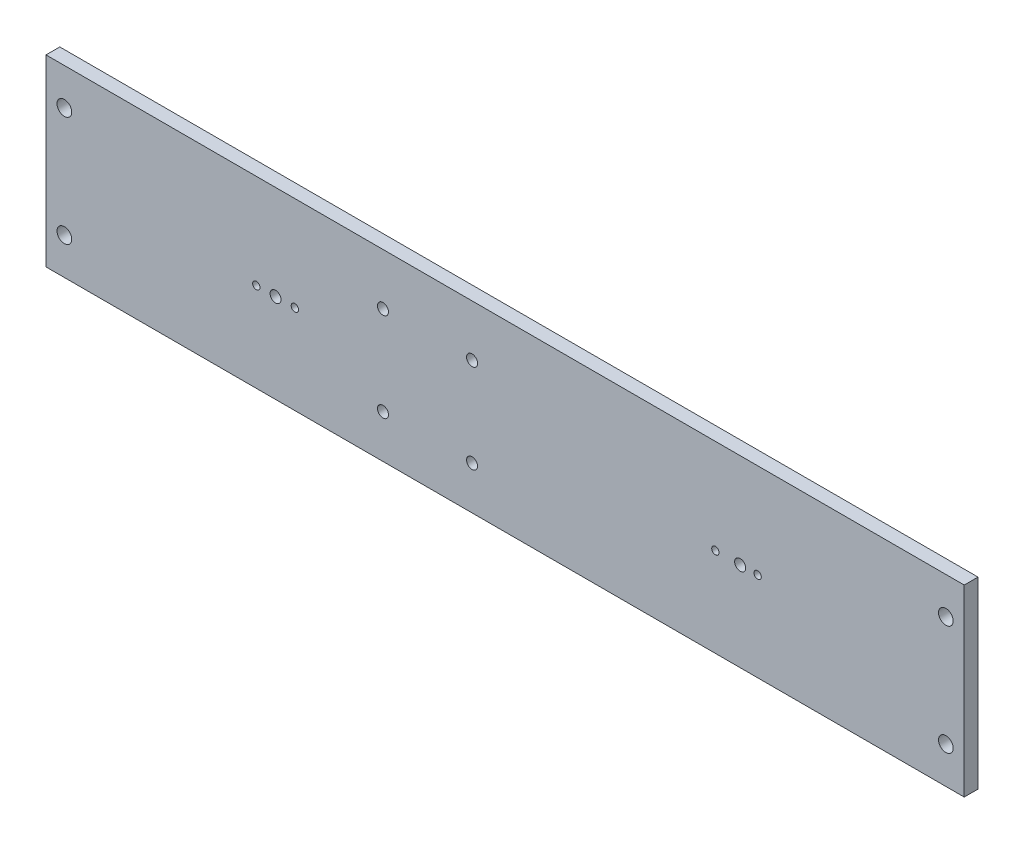
SolidWorks part; units mm, degrees
ref_plane "Front Plane" through (0, 0, 0) normal (0, 0, 1) x (1, 0, 0)
ref_plane "Top Plane" through (0, 0, 0) normal (0, 1, 0) x (1, 0, 0)
ref_plane "Right Plane" through (0, 0, 0) normal (1, 0, 0) x (0, 0, -1)
sketch "Sketch2" plane through (0, 0, 0) normal (0, 0, 1) x (1, 0, 0)
  line L1 (0, 100) -> (500, 100)
  line L2 (0, 100) -> (0, 0)
  line L3 (0, 0) -> (500, 0)
  line L4 (500, 100) -> (500, 0)
  dimension "D1" = 100
  dimension "D2" = 500
extrude "Boss-Extrude1" add sketch "Sketch2" along normal blind 7.5
sketch "Sketch8" plane through (0, 0, 7.5) normal (0, 0, 1) x (1, 0, 0)
  circle A0 centre (183.5, 23.5) radius 3
  circle A2 centre (183.5, 72) radius 3
  circle A3 centre (232, 72) radius 3
  circle A4 centre (232, 23.5) radius 3
  dimension "D1" = 2
  dimension "D2" = 2
extrude "Cut-Extrude2" cut sketch "Sketch8" against normal through all
sketch "Sketch9" plane through (0, 0, 7.5) normal (0, 0, 1) x (1, 0, 0)
  circle A0 centre (125, 48.5) radius 3
  circle A1 centre (135.5, 48.5) radius 2
  circle A2 centre (114.5, 48.5) radius 2
  circle A3 centre (378, 48.5) radius 3
  circle A4 centre (387.5, 48.5) radius 2
  circle A5 centre (364.5, 48.5) radius 2
  point P6 (0, 0)
  point P7 (0, 0)
  point P14 (0, 0)
  point P15 (0, 0)
  point P16 (0, 0)
  point P17 (0, 0)
  point P18 (0, 0)
  point P19 (0, 0)
  point P20 (0, 0)
extrude "Cut-Extrude3" cut sketch "Sketch9" against normal through all
sketch "Sketch11" plane through (0, 0, 7.5) normal (0, 0, 1) x (1, 0, 0)
  circle A0 centre (10, 80) radius 4
  circle A1 centre (10, 20) radius 4
  circle A2 centre (490, 20) radius 4
  circle A3 centre (490, 80) radius 4
  point P2 (0, 0)
  dimension "D1" = 2
  dimension "D2" = 60
extrude "Cut-Extrude4" cut sketch "Sketch11" against normal through all
